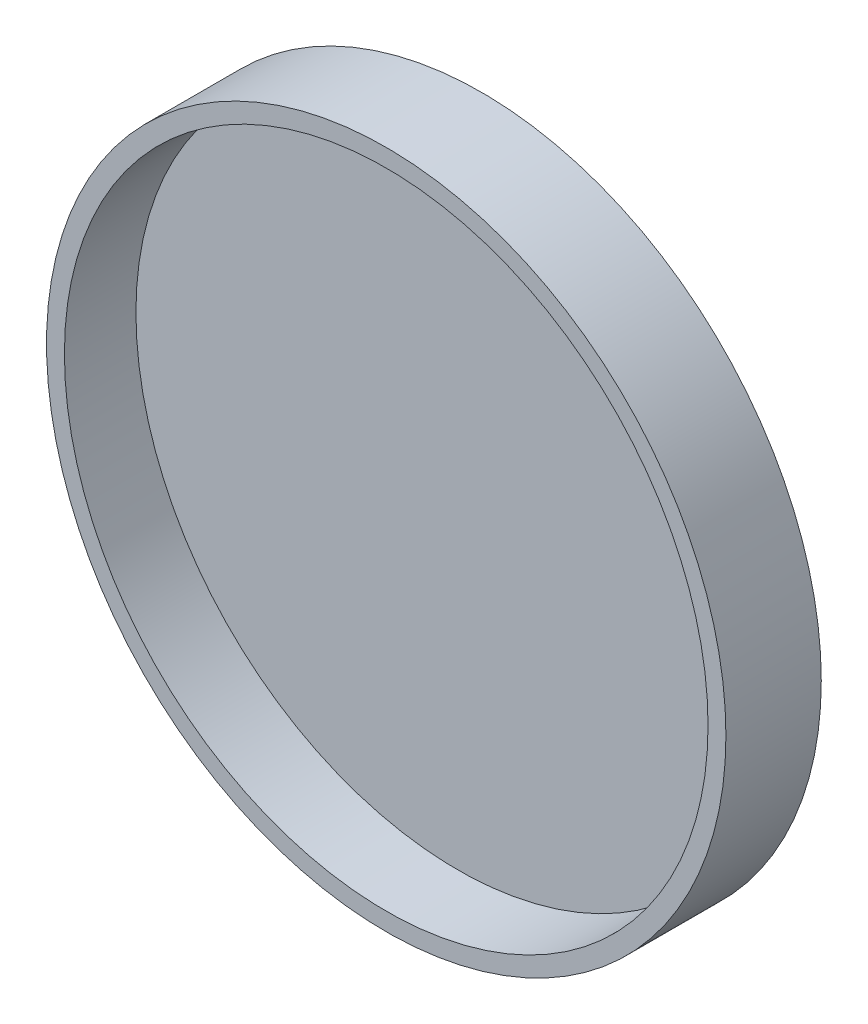
SolidWorks part; units mm, degrees
ref_plane "Front" through (0, 0, 0) normal (0, 0, 1) x (1, 0, 0)
ref_plane "Top" through (0, 0, 0) normal (0, 1, 0) x (1, 0, 0)
ref_plane "Right" through (0, 0, 0) normal (1, 0, 0) x (0, 0, -1)
sketch "Эскиз1" plane through (0, 0, 0) normal (0, 0, 1) x (1, 0, 0)
  circle A0 centre (0, 0) radius 6.5
  dimension "D1" = 13
extrude "Бобышка-Вытянуть1" add sketch "Эскиз1" along normal blind 0.5
sketch "Эскиз2" plane through (0, 0, 0.5) normal (0, 0, 1) x (1, 0, 0)
  circle A0 centre (0, 0) radius 7.75
  dimension "D1" = 15.5
extrude "Бобышка-Вытянуть2" add sketch "Эскиз2" along normal blind 2.5
sketch "Эскиз3" plane through (0, 0, 3) normal (0, 0, 1) x (1, 0, 0)
  circle A0 centre (0, 0) radius 9
  dimension "D1" = 18
extrude "Бобышка-Вытянуть3" add sketch "Эскиз3" along normal blind 2
sketch "Эскиз4" plane through (0, 0, 5) normal (0, 0, 1) x (1, 0, 0)
  circle A0 centre (0, 0) radius 14.25
  dimension "D1" = 28.5
extrude "Бобышка-Вытянуть4" add sketch "Эскиз4" along normal blind 1
sketch "Эскиз5" plane through (0, 0, 6) normal (0, 0, 1) x (1, 0, 0)
  circle A0 centre (0, 0) radius 13.5
  circle A1 centre (0, 0) radius 14.25
  circle A2 centre (0, 0) radius 14.25 construction
  dimension "D1" = 27
extrude "Бобышка-Вытянуть5" add sketch "Эскиз5" along normal blind 3
